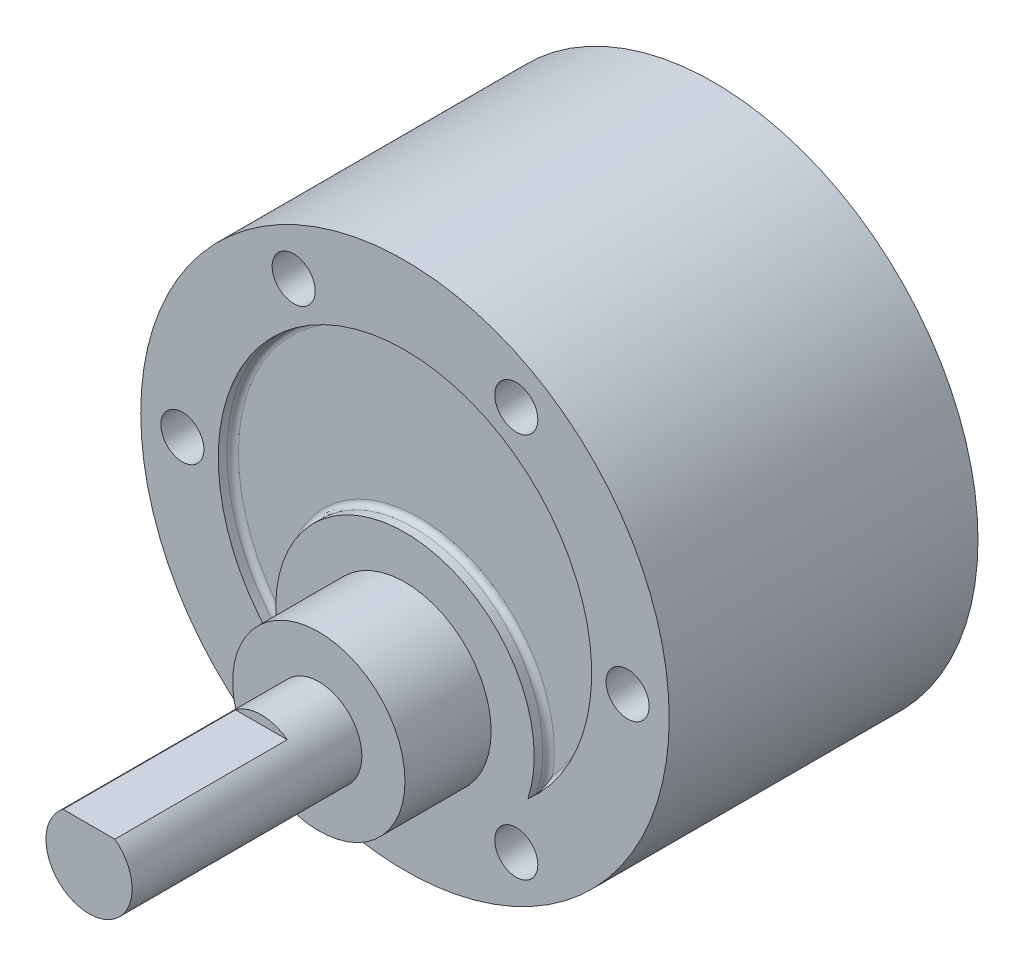
SolidWorks part; units mm, degrees
material "3.0515 (EN-AW 3103)"
ref_plane "Alzado" through (0, 0, 0) normal (0, 0, 1) x (1, 0, 0)
ref_plane "Planta" through (0, 0, 0) normal (0, 1, 0) x (1, 0, 0)
ref_plane "Vista lateral" through (0, 0, 0) normal (1, 0, 0) x (0, 0, -1)
sketch "Croquis1" plane through (0, 0, 0) normal (0, 0, 1) x (1, 0, 0)
  circle A0 centre (0, 0) radius 18.4
  dimension "D1" = 36.8
extrude "Saliente-Extruir1" add sketch "Croquis1" along normal blind 21.5
sketch "Croquis3" plane through (0, 0, 21.5) normal (0, 0, 1) x (1, 0, 0)
  line L0 (0, 0) -> (0, -7) construction
  circle A0 centre (0, -7) radius 6
  dimension "D2" = 12
  dimension "D1" = 7
extrude "Saliente-Extruir2" add sketch "Croquis3" along normal blind 6
sketch "Croquis4" plane through (0, 0, 27.5) normal (0, 0, 1) x (1, 0, 0)
  line L1 (0, -4.6) -> (1.8, -4.6) construction
  line L2 (0, -4.6) -> (-1.8, -4.6) construction
  line L3 (1.8, -4.6) -> (-1.8, -4.6)
  arc A0 (-1.8, -4.6) -> (1.8, -4.6) centre (0, -7) ccw
  dimension "D1" = 6
extrude "Saliente-Extruir3" add sketch "Croquis4" along normal blind 16
sketch "Croquis5" plane through (0, 0, 27.5) normal (0, 0, 1) x (1, 0, 0)
  line L0 (-1.8, -4.6) -> (1.8, -4.6)
  arc A0 (1.8, -4.6) -> (-1.8, -4.6) centre (0, -7) ccw
extrude "Saliente-Extruir4" add sketch "Croquis5" along normal blind 4
sketch "Croquis6" plane through (0, 0, 21.5) normal (0, 0, 1) x (1, 0, 0)
  arc A0 (8.558, -9.7857) -> (-8.558, -9.7857) centre (0, 0) ccw
  arc A1 (8.558, -9.7857) -> (-8.558, -9.7857) centre (0, -7) ccw
  dimension "D1" = 18
extrude "Cortar-Extruir1" cut sketch "Croquis6" against normal blind 1
fillet "Redondeo4" radius 0.4 2 edges at (0, 13, 20.5) (0, 2, 20.5)
sketch "Croquis7" plane through (0, 0, 21.5) normal (0, 0, 1) x (1, 0, 0)
  line L0 (-13, 0) -> (-18.4, 0) construction
  line L6 (-18.4, 0) -> (-13, 0) construction
  line L7 (-13, 0) -> (-15.5, 0) construction
  circle A0 centre (0, 0) radius 18.4 construction
  arc A1 (8.558, -9.7857) -> (-8.558, -9.7857) centre (0, 0) ccw construction
  circle A2 centre (-15.5, 0) radius 1.5
  circle A12 centre (-7.75, 13.4234) radius 1.5
  circle A13 centre (7.75, 13.4234) radius 1.5
  circle A14 centre (15.5, 0) radius 1.5
  circle A15 centre (7.75, -13.4234) radius 1.5
  circle A16 centre (-7.75, -13.4234) radius 1.5
  dimension "D4" = 2.5
  dimension "D5" = 3
  dimension "D8" = 6
extrude "Cortar-Extruir2" cut sketch "Croquis7" against normal blind 3
